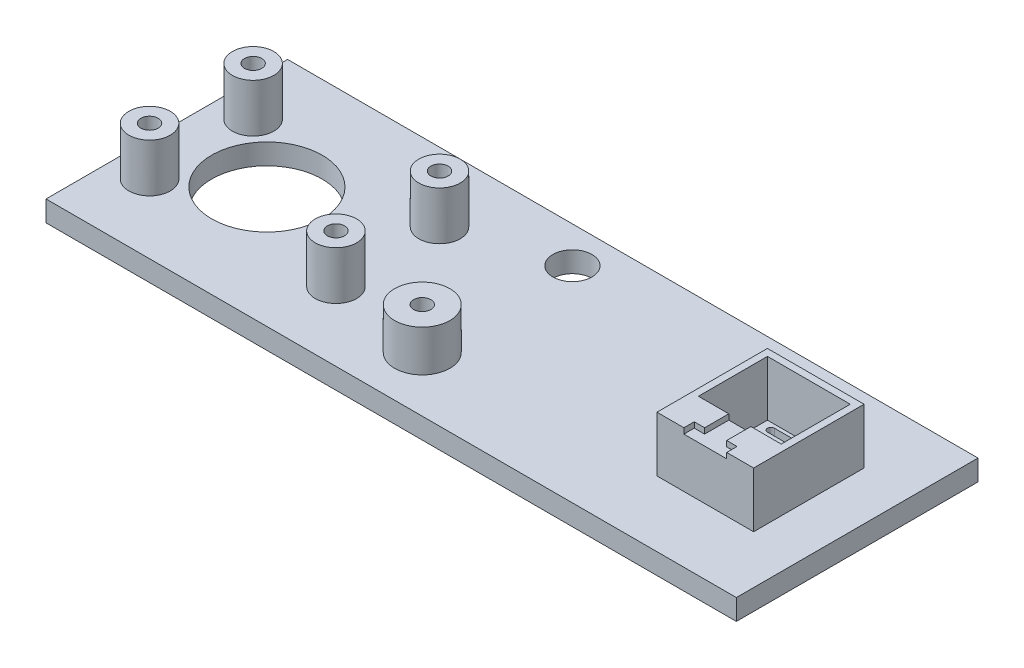
SolidWorks part; units mm, degrees
ref_plane "Front Plane" through (0, 0, 0) normal (0, 0, 1) x (1, 0, 0)
ref_plane "Top Plane" through (0, 0, 0) normal (0, 1, 0) x (1, 0, 0)
ref_plane "Right Plane" through (0, 0, 0) normal (1, 0, 0) x (0, 0, -1)
sketch "Sketch1" plane through (0, 0, 0) normal (0, 1, 0) x (1, 0, 0)
  line L1 (0, 0) -> (100, 0)
  line L2 (0, 0) -> (0, 35)
  line L3 (0, 35) -> (100, 35)
  line L4 (100, 0) -> (100, 35)
  dimension "D1" = 100
  dimension "D2" = 35
extrude "Boss-Extrude1" add sketch "Sketch1" along normal blind 3
sketch "Sketch2" plane through (0, 3, 0) normal (0, 1, 0) x (1, 0, 0)
  line L0 (5, 25) -> (5, 10) construction
  line L1 (5, 17.5) -> (14.5, 17.5) construction
  line L2 (0, 35) -> (0, 0) construction
  circle A0 centre (5, 25) radius 3
  circle A1 centre (5, 10) radius 3
  circle A2 centre (32, 10) radius 3
  circle A3 centre (32, 25) radius 3
  circle A4 centre (14.5, 17.5) radius 8
  point P15 (0, 17.5)
  dimension "D1" = 6
  dimension "D2" = 27
  dimension "D3" = 15
  dimension "D5" = 16
  dimension "D4" = 9.5
  dimension "D6" = 5
extrude "Boss-Extrude2" add sketch "Sketch2" along normal blind 7 contours A3 | A1 | A2 | A0
sketch "Sketch3" plane through (0, 3, 0) normal (0, 1, 0) x (1, 0, 0)
  circle A0 centre (14.5, 17.5) radius 8 construction
  circle A1 centre (14.5, 17.5) radius 8
extrude "Cut-Extrude2" cut sketch "Sketch3" against normal up to next
sketch "Sketch4" plane through (0, 10, 0) normal (0, 1, 0) x (1, 0, 0)
  circle A0 centre (32, 25) radius 1.25
  circle A1 centre (32, 10) radius 1.25
  circle A2 centre (5, 10) radius 1.25
  circle A3 centre (5, 25) radius 1.25
  dimension "D1" = 2.5
extrude "Cut-Extrude3" cut sketch "Sketch4" against normal blind 6
sketch "Sketch5" plane through (0, 3, 0) normal (0, 1, 0) x (1, 0, 0)
  line L0 (0, 35) -> (0, 0) construction
  line L1 (0, 0) -> (100, 0) construction
  circle A0 centre (46.5, 8) radius 4
  circle A1 centre (46.5, 8) radius 1.25
  dimension "D1" = 8
  dimension "D2" = 2.5
  dimension "D3" = 46.5
  dimension "D4" = 8
extrude "Boss-Extrude3" add sketch "Sketch5" along normal blind 6
sketch "Sketch6" plane through (0, 0, 0) normal (0, -1, 0) x (1, 0, 0)
  line L0 (46.5, -31.83) -> (46.5, -27.67) construction
  line L1 (45.75, -31.83) -> (47.25, -31.83) construction
  line L2 (47.25, -27.67) -> (45.75, -27.67) construction
  circle A0 centre (46.5, -29.75) radius 2.83
  arc A2 (47.25, -31.83) -> (47.25, -27.67) centre (47.25, -29.75) ccw construction
  arc A3 (45.75, -27.67) -> (45.75, -31.83) centre (45.75, -29.75) ccw construction
  point P2 (0, 0)
  point P3 (46.5, -29.75)
extrude "Cut-Extrude4" cut sketch "Sketch6" against normal up to next
sketch "Sketch8" plane through (0, 3, 0) normal (0, 1, 0) x (1, 0, 0)
  line L0 (80, 14.5) -> (80, 24.5)
  line L1 (80, 24.5) -> (92, 24.5)
  line L2 (92, 24.5) -> (92, 14.5)
  line L3 (92, 14.5) -> (80, 14.5)
  line L4 (79, 25.5) -> (79, 9.5)
  line L5 (79, 9.5) -> (93, 9.5)
  line L6 (93, 9.5) -> (93, 25.5)
  line L7 (93, 25.5) -> (79, 25.5)
  line L8 (100, 0) -> (100, 35) construction
  point P10 (100, 17.5)
  point P11 (93, 17.5)
  dimension "D1" = 1
  dimension "D2" = 1
  dimension "D3" = 1
  dimension "D4" = 10
  dimension "D5" = 16
  dimension "D6" = 14
  dimension "D7" = 7
extrude "Boss-Extrude4" add sketch "Sketch8" along normal blind 8
sketch "Sketch9" plane through (0, 11, 0) normal (0, 1, 0) x (1, 0, 0)
  line L0 (86, 14.5) -> (86, 9.5) construction
  line L1 (80, 14.5) -> (92, 14.5) construction
  line L2 (79, 9.5) -> (93, 9.5) construction
  line L3 (84.4, 14.5) -> (84.4, 11)
  line L4 (84.4, 11) -> (82.9, 11)
  line L5 (82.9, 11) -> (82.9, 9.5)
  line L6 (89.1, 11) -> (89.1, 9.5)
  line L7 (87.6, 11) -> (89.1, 11)
  line L8 (87.6, 14.5) -> (87.6, 11)
  line L9 (84.4, 14.5) -> (87.6, 14.5)
  line L10 (89.1, 9.5) -> (82.9, 9.5)
  dimension "D1" = 1.6
  dimension "D2" = 3.1
  dimension "D3" = 3.5
extrude "Cut-Extrude5" cut sketch "Sketch9" against normal blind 0.8
sketch "Sketch10" plane through (0, 3, 0) normal (0, 1, 0) x (1, 0, 0)
  line L0 (81.5, 23.5) -> (90.5, 23.5) construction
  line L1 (81.5, 24) -> (90.5, 24)
  line L2 (81.5, 23) -> (90.5, 23)
  line L3 (92, 24.5) -> (80, 24.5) construction
  line L4 (81.5, 21.5) -> (90.5, 21.5) construction
  line L5 (81.5, 22) -> (90.5, 22)
  line L6 (81.5, 21) -> (90.5, 21)
  line L7 (81.5, 19.5) -> (90.5, 19.5) construction
  line L8 (81.5, 20) -> (90.5, 20)
  line L9 (81.5, 19) -> (90.5, 19)
  line L10 (81.5, 17.5) -> (90.5, 17.5) construction
  line L11 (81.5, 18) -> (90.5, 18)
  line L12 (81.5, 17) -> (90.5, 17)
  line L13 (81.5, 15.5) -> (90.5, 15.5) construction
  line L14 (81.5, 16) -> (90.5, 16)
  line L15 (81.5, 15) -> (90.5, 15)
  arc A0 (81.5, 24) -> (81.5, 23) centre (81.5, 23.5) ccw
  arc A1 (90.5, 23) -> (90.5, 24) centre (90.5, 23.5) ccw
  arc A2 (81.5, 22) -> (81.5, 21) centre (81.5, 21.5) ccw
  arc A3 (90.5, 21) -> (90.5, 22) centre (90.5, 21.5) ccw
  arc A4 (81.5, 20) -> (81.5, 19) centre (81.5, 19.5) ccw
  arc A5 (90.5, 19) -> (90.5, 20) centre (90.5, 19.5) ccw
  arc A6 (81.5, 18) -> (81.5, 17) centre (81.5, 17.5) ccw
  arc A7 (90.5, 17) -> (90.5, 18) centre (90.5, 17.5) ccw
  arc A8 (81.5, 16) -> (81.5, 15) centre (81.5, 15.5) ccw
  arc A9 (90.5, 15) -> (90.5, 16) centre (90.5, 15.5) ccw
  point P2 (86, 23.5)
  point P10 (86, 24.5)
  point P14 (86, 21.5)
  point P21 (86, 19.5)
  point P28 (86, 17.5)
  point P35 (86, 15.5)
  dimension "D2" = 0.5
  dimension "D1" = 9
  dimension "D3" = 1
  dimension "D4" = 5
extrude "Cut-Extrude6" cut sketch "Sketch10" against normal up to next
